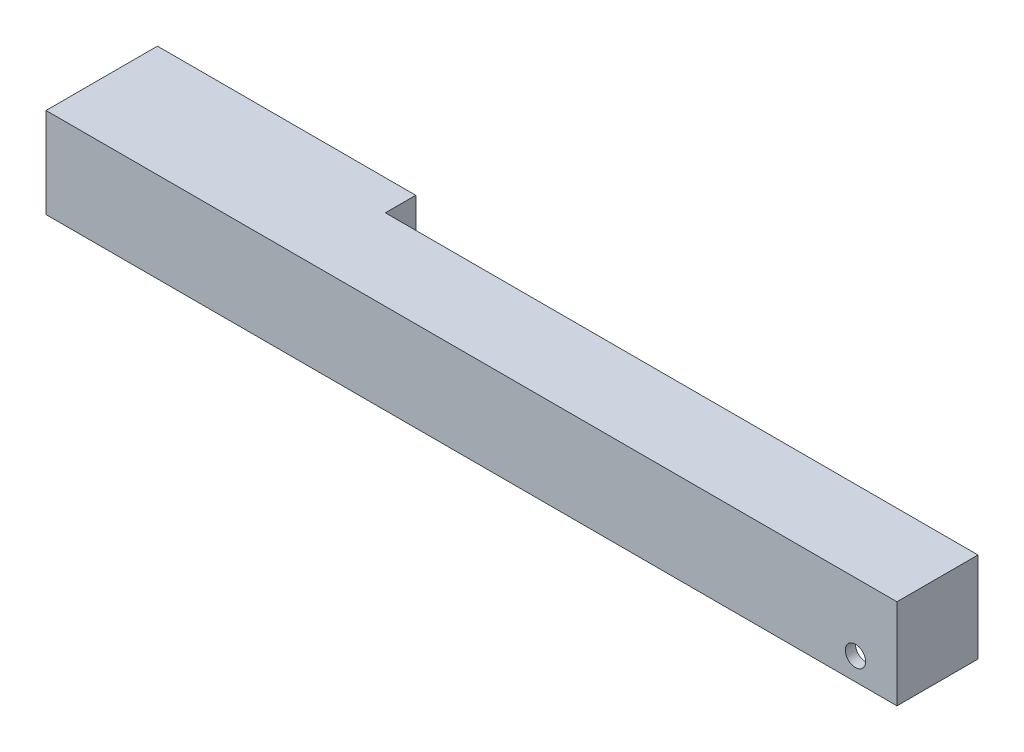
SolidWorks part; units mm, degrees
ref_plane "Front Plane" through (0, 0, 0) normal (0, 0, 1) x (1, 0, 0)
ref_plane "Top Plane" through (0, 0, 0) normal (0, 1, 0) x (1, 0, 0)
ref_plane "Right Plane" through (0, 0, 0) normal (1, 0, 0) x (0, 0, -1)
sketch "Sketch1" plane through (0, 0, 0) normal (0, 1, 0) x (1, 0, 0)
  line L1 (-84, -11) -> (84, -11)
  line L2 (-84, -11) -> (-84, 11)
  line L3 (-84, 11) -> (84, 11)
  line L4 (84, -11) -> (84, 11)
  line L5 (-84, -11) -> (84, 11) construction
  line L6 (-84, 11) -> (84, -11) construction
  point P0 (0, 0)
  dimension "D1" = 22
  dimension "D2" = 168
extrude "Boss-Extrude1" add sketch "Sketch1" against normal blind 17.8 contours L2 L3 L4 L1
sketch "Sketch8" plane through (0, 0, 11) normal (0, 0, 1) x (1, 0, 0)
  line L0 (84, 0) -> (51.2, -17.8) construction
  line L1 (-84, -17.8) -> (84, -17.8) construction
  line L3 (67.6, -8.9) -> (84, -8.9) construction
  line L4 (84, -17.8) -> (84, 0) construction
  line L5 (75.8, -8.9) -> (75.8, -17.8) construction
  circle A0 centre (75.8, -13.35) radius 2
  dimension "D1" = 4
extrude "Cut-Extrude4" cut sketch "Sketch8" against normal up to surface (22 mm away) up to face at (0, -8.9, -11)
sketch "Sketch5" plane through (0, 0, 0) normal (0, 1, 0) x (1, 0, 0)
  line L0 (-84, 11) -> (84, 11) construction
  line L1 (-33, 11) -> (84, 11)
  line L2 (-33, 11) -> (-33, 5)
  line L3 (-33, 5) -> (84, 5)
  line L4 (84, 11) -> (84, 5)
  line L5 (-33, 11) -> (84, 5) construction
  line L6 (-33, 5) -> (84, 11) construction
  line L7 (84, -11) -> (84, 11) construction
  point P0 (25.5, 8)
  dimension "D1" = 117
  dimension "D2" = 6
extrude "Cut-Extrude2" cut sketch "Sketch5" against normal up to surface (17.8 mm away) up to face at (0, -17.8, 0)
sketch "Sketch6" plane through (0, -17.8, 0) normal (0, -1, 0) x (1, 0, 0)
  line L0 (-82, 9) -> (-82, -9)
  line L1 (-82, -9) -> (-35, -9)
  line L2 (-35, -9) -> (-35, -3)
  line L3 (-35, -3) -> (82, -3)
  line L4 (82, -3) -> (82, 9)
  line L5 (82, 9) -> (-82, 9)
  line L6 (-84, 11) -> (84, 11) construction
  line L7 (-84, 11) -> (-84, -11) construction
  line L8 (-84, -11) -> (-33, -11) construction
  line L9 (-33, -5) -> (-33, -11) construction
  line L10 (84, -5) -> (-33, -5) construction
  line L11 (84, 11) -> (84, -5) construction
  dimension "D1" = 2
  dimension "D2" = 2
  dimension "D3" = 2
  dimension "D4" = 2
  dimension "D5" = 2
  dimension "D6" = 2
extrude "Cut-Extrude3" cut sketch "Sketch6" against normal offset from surface (15.8 mm away) 2 up to face at (-11, 0, -1.6667)
sketch "Sketch7" plane through (0, 0, -9) normal (0, 0, 1) x (1, 0, 0)
  line L0 (-82, -12.3) -> (-35, -12.3)
  line L1 (-82, -12.3) -> (-82, -14.3)
  line L2 (-35, -12.3) -> (-35, -14.3)
  line L3 (-82, -14.3) -> (-35, -14.3)
  line L4 (-82, -2) -> (-82, -17.8) construction
  line L5 (-35, -2) -> (-35, -17.8) construction
  line L7 (-82, -17.8) -> (-35, -17.8) construction
  dimension "D1" = 3.5
  dimension "D2" = 2
extrude "Boss-Extrude3" add sketch "Sketch7" along normal up to surface (18 mm away) up to face at (0, -9.9, 9)
